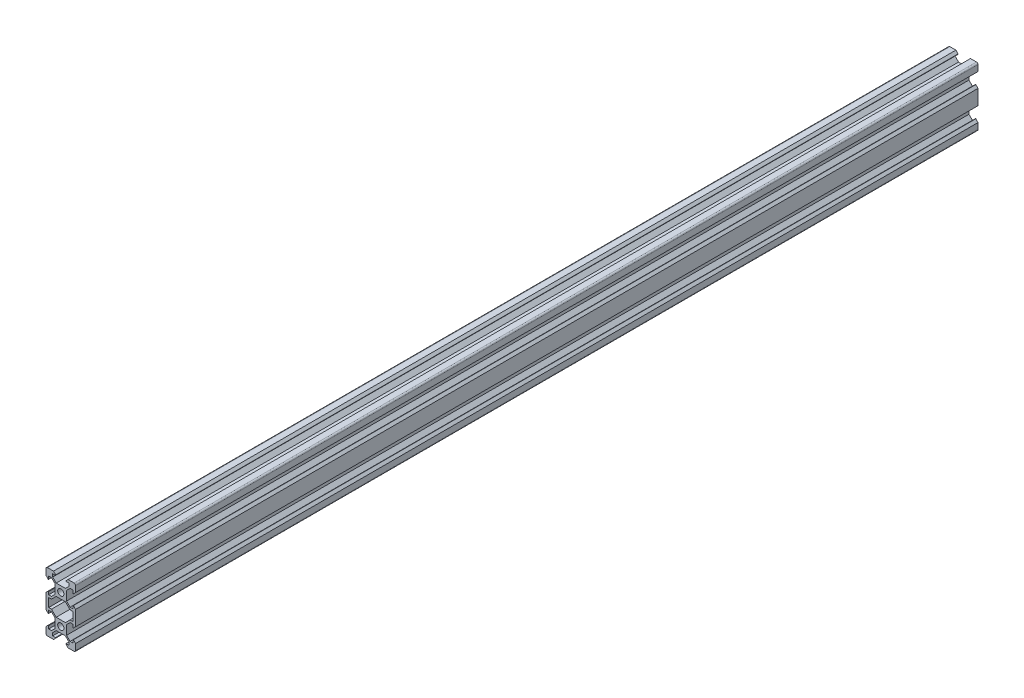
SolidWorks part; units mm, degrees
ref_plane "Front Plane" through (0, 0, 0) normal (0, 0, 1) x (1, 0, 0)
ref_plane "Top Plane" through (0, 0, 0) normal (0, 1, 0) x (1, 0, 0)
ref_plane "Right Plane" through (0, 0, 0) normal (1, 0, 0) x (0, 0, -1)
sketch "Sketch1" plane through (0, 0, 0) normal (0, 1, 0) x (1, 0, 0)
  line L0 (0, -304.8) -> (0, 304.8)
  point P4 (0, 0)
  dimension "D1" = 609.6
other "Vslot2040 2040(1)"
ref_plane "Plane1" through (0, 0, 304.8) normal (0, 0, -1) x (-1, 0, 0)
sketch "Sketch11" plane through (0, 0, 304.8) normal (0, 0, -1) x (-1, 0, 0)
  line L12 (3.125, 6.1) -> (6.275, 2.95)
  line L13 (6.275, 2.95) -> (8.2, 2.95)
  line L14 (8.2, 2.95) -> (8.2, -2.95)
  line L15 (8.2, -2.95) -> (6.275, -2.95)
  line L16 (3.125, -6.1) -> (6.275, -2.95)
  line L17 (3.125, -6.1) -> (-3.125, -6.1)
  line L18 (-3.125, -6.1) -> (-6.275, -2.95)
  line L19 (-8.2, -2.95) -> (-6.275, -2.95)
  line L20 (-8.2, 2.95) -> (-8.2, -2.95)
  line L21 (-6.275, 2.95) -> (-8.2, 2.95)
  line L22 (-3.125, 6.1) -> (-6.275, 2.95)
  line L23 (3.125, 6.1) -> (-3.125, 6.1)
  line L128 (5.5, -18.2) -> (3.6078, -18.2)
  line L129 (3.4664, -18.5414) -> (4.925, -20)
  line L130 (4.925, -20) -> (9, -20)
  line L131 (10, -19) -> (10, -14.925)
  line L132 (10, -14.925) -> (8.5414, -13.4664)
  line L133 (8.2, -13.6078) -> (8.2, -15.5)
  line L134 (8.2, -15.5) -> (6.275, -15.5)
  line L135 (6.275, -15.5) -> (3.9, -13.125)
  line L136 (3.9, -13.125) -> (3.9, -6.875)
  line L137 (3.9, -6.875) -> (6.275, -4.5)
  line L138 (6.275, -4.5) -> (8.2, -4.5)
  line L139 (8.2, -4.5) -> (8.2, -6.3922)
  line L140 (8.5414, -6.5336) -> (10, -5.075)
  line L141 (10, -5.075) -> (10, 5.075)
  line L142 (10, 5.075) -> (8.5414, 6.5336)
  line L143 (8.2, 6.3922) -> (8.2, 4.5)
  line L144 (8.2, 4.5) -> (6.275, 4.5)
  line L145 (6.275, 4.5) -> (3.9, 6.875)
  line L146 (3.9, 6.875) -> (3.9, 13.125)
  line L147 (3.9, 13.125) -> (6.275, 15.5)
  line L148 (6.275, 15.5) -> (8.2, 15.5)
  line L149 (8.2, 15.5) -> (8.2, 13.6078)
  line L150 (8.5414, 13.4664) -> (10, 14.925)
  line L151 (10, 14.925) -> (10, 19)
  line L152 (9, 20) -> (4.925, 20)
  line L153 (4.925, 20) -> (3.4664, 18.5414)
  line L154 (3.6078, 18.2) -> (5.5, 18.2)
  line L155 (5.5, 18.2) -> (5.5, 16.275)
  line L156 (5.5, 16.275) -> (3.125, 13.9)
  line L157 (3.125, 13.9) -> (-3.125, 13.9)
  line L158 (-3.125, 13.9) -> (-5.5, 16.275)
  line L159 (-5.5, 16.275) -> (-5.5, 18.2)
  line L160 (-5.5, 18.2) -> (-3.6078, 18.2)
  line L161 (-3.4664, 18.5414) -> (-4.925, 20)
  line L162 (-4.925, 20) -> (-9, 20)
  line L163 (-10, 19) -> (-10, 14.925)
  line L164 (-10, 14.925) -> (-8.5414, 13.4664)
  line L165 (-8.2, 13.6078) -> (-8.2, 15.5)
  line L166 (-8.2, 15.5) -> (-6.275, 15.5)
  line L167 (-6.275, 15.5) -> (-3.9, 13.125)
  line L168 (-3.9, 13.125) -> (-3.9, 6.875)
  line L169 (-3.9, 6.875) -> (-6.275, 4.5)
  line L170 (-6.275, 4.5) -> (-8.2, 4.5)
  line L171 (-8.2, 4.5) -> (-8.2, 6.3922)
  line L172 (-8.5414, 6.5336) -> (-10, 5.075)
  line L173 (-10, 5.075) -> (-10, -5.075)
  line L174 (-10, -5.075) -> (-8.5414, -6.5336)
  line L175 (-8.2, -6.3922) -> (-8.2, -4.5)
  line L176 (-8.2, -4.5) -> (-6.275, -4.5)
  line L177 (-6.275, -4.5) -> (-3.9, -6.875)
  line L178 (-3.9, -6.875) -> (-3.9, -13.125)
  line L179 (-3.9, -13.125) -> (-6.275, -15.5)
  line L180 (-6.275, -15.5) -> (-8.2, -15.5)
  line L181 (-8.2, -15.5) -> (-8.2, -13.6078)
  line L182 (-8.5414, -13.4664) -> (-10, -14.925)
  line L183 (-10, -14.925) -> (-10, -19)
  line L184 (-9, -20) -> (-4.925, -20)
  line L185 (-4.925, -20) -> (-3.4664, -18.5414)
  line L186 (-3.6078, -18.2) -> (-5.5, -18.2)
  line L187 (-5.5, -18.2) -> (-5.5, -16.275)
  line L188 (-5.5, -16.275) -> (-3.125, -13.9)
  line L189 (-3.125, -13.9) -> (3.125, -13.9)
  line L190 (3.125, -13.9) -> (5.5, -16.275)
  line L191 (5.5, -16.275) -> (5.5, -18.2)
  circle A2 centre (0, -10) radius 2.1
  circle A3 centre (0, 10) radius 2.1
  arc A32 (3.6078, -18.2) -> (3.4664, -18.5414) centre (3.6078, -18.4) ccw
  arc A33 (9, -20) -> (10, -19) centre (9, -19) ccw
  arc A34 (8.5414, -13.4664) -> (8.2, -13.6078) centre (8.4, -13.6078) ccw
  arc A35 (8.2, -6.3922) -> (8.5414, -6.5336) centre (8.4, -6.3922) ccw
  arc A36 (8.5414, 6.5336) -> (8.2, 6.3922) centre (8.4, 6.3922) ccw
  arc A37 (8.2, 13.6078) -> (8.5414, 13.4664) centre (8.4, 13.6078) ccw
  arc A38 (10, 19) -> (9, 20) centre (9, 19) ccw
  arc A39 (3.4664, 18.5414) -> (3.6078, 18.2) centre (3.6078, 18.4) ccw
  arc A40 (-3.6078, 18.2) -> (-3.4664, 18.5414) centre (-3.6078, 18.4) ccw
  arc A41 (-9, 20) -> (-10, 19) centre (-9, 19) ccw
  arc A42 (-8.5414, 13.4664) -> (-8.2, 13.6078) centre (-8.4, 13.6078) ccw
  arc A43 (-8.2, 6.3922) -> (-8.5414, 6.5336) centre (-8.4, 6.3922) ccw
  arc A44 (-8.5414, -6.5336) -> (-8.2, -6.3922) centre (-8.4, -6.3922) ccw
  arc A45 (-8.2, -13.6078) -> (-8.5414, -13.4664) centre (-8.4, -13.6078) ccw
  arc A46 (-10, -19) -> (-9, -20) centre (-9, -19) ccw
  arc A47 (-3.4664, -18.5414) -> (-3.6078, -18.2) centre (-3.6078, -18.4) ccw
  point P43 (0, 0)
